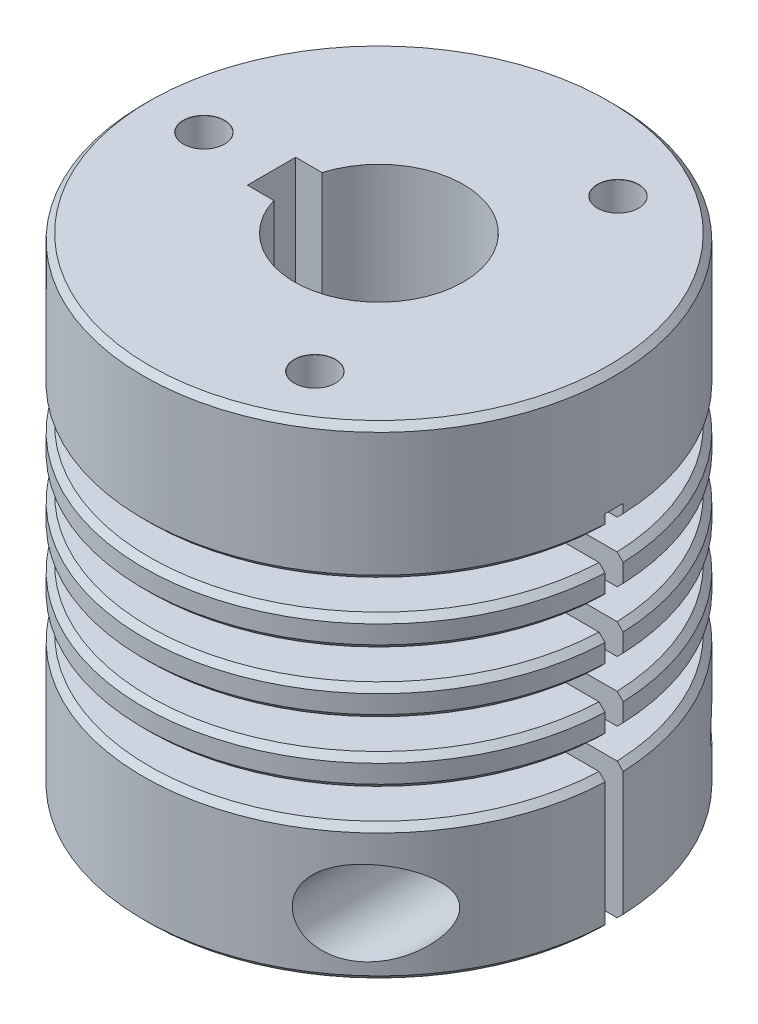
SolidWorks part; units mm, degrees
material "6061-T6 (SS)"
ref_plane "Front Plane" through (0, 0, 0) normal (0, 0, 1) x (1, 0, 0)
ref_plane "Top Plane" through (0, 0, 0) normal (0, 1, 0) x (1, 0, 0)
ref_plane "Right Plane" through (0, 0, 0) normal (1, 0, 0) x (0, 0, -1)
sketch "Sketch3" plane through (0, 0, 0) normal (0, 1, 0) x (1, 0, 0)
  line L0 (-14, 0) -> (-17.8, 0) construction
  line L1 (-17.8, 4) -> (-17.8, -4)
  line L2 (-17.8, 4) -> (-10.3, 4)
  line L3 (-17.8, -4) -> (-10.3, -4)
  line L4 (-10.3, 4) -> (-10.3, -4)
  line L5 (-14, 0) -> (-10.3, 0) construction
  circle A0 centre (0, 0) radius 39 construction
  circle A1 centre (0, 0) radius 14 construction
  point P9 (-17.8, 0)
  dimension "D1" = 78
  dimension "D2" = 28
  dimension "D3" = 8
  dimension "D4" = 3.8
  dimension "D5" = 3.7
sketch "Sketch4" plane through (0, 0, 0) normal (0, 1, 0) x (1, 0, 0)
  line L0 (-17.8, 4) -> (-17.8, -4) construction
  line L1 (-17.8, 4) -> (-17.8, -4)
  line L2 (-17.8, 4) -> (-13.4164, 4)
  line L3 (-17.8, 4) -> (-10.3, 4) construction
  line L4 (-17.8, -4) -> (-13.4164, -4)
  circle A0 centre (0, 0) radius 14 construction
  circle A1 centre (0, 0) radius 39 construction
  arc A2 (-13.4164, -4) -> (-13.4164, 4) centre (0, 0) ccw
  circle A3 centre (0, 0) radius 39
extrude "Boss-Extrude1" add sketch "Sketch4" along normal blind 80
sketch "Sketch7" plane through (0, 0, 0) normal (0, -1, 0) x (1, 0, 0)
  line L0 (14, 0) -> (39, 0) construction
  line L2 (11.5, 1.5) -> (41.5, 1.5)
  line L3 (11.5, 1.5) -> (11.5, -1.5)
  line L4 (11.5, -1.5) -> (41.5, -1.5)
  line L5 (41.5, 1.5) -> (41.5, -1.5)
  line L6 (11.5, 1.5) -> (41.5, -1.5) construction
  line L7 (11.5, -1.5) -> (41.5, 1.5) construction
  arc A0 (-13.4164, -4) -> (-13.4164, 4) centre (0, 0) ccw construction
  circle A1 centre (0, 0) radius 39 construction
  point P8 (26.5, 0)
  dimension "D1" = 3
  dimension "D2" = 30
extrude "Cut-Extrude1" cut sketch "Sketch7" against normal blind 60
sketch "Sketch9" plane through (0, 0, 0) normal (0, 0, 1) x (1, 0, 0)
  line L0 (26.4453, 0) -> (26.4453, 10) construction
  line L5 (13.9194, 60) -> (13.9194, 0)
  line L6 (13.9194, 0) -> (38.9711, 0)
  line L7 (38.9711, 0) -> (38.9711, 60)
  line L10 (13.9194, 0) -> (38.9711, 0) construction
  line L17 (38.9711, 60) -> (13.9194, 60)
  circle A0 centre (26.4453, 10) radius 3.4
  dimension "D2" = 6.8
  dimension "D3" = 10
  dimension "D1" = 0
extrude "Cut-Extrude2" cut sketch "Sketch9" against normal through all
sketch "Sketch10" plane through (0, 0, 0) normal (0, 0, 1) x (1, 0, 0)
  circle A1 centre (26.4453, 10) radius 4
  point P0 (26.4453, 10)
  dimension "D1" = 8
extrude "Cut-Extrude3" cut sketch "Sketch10" along normal through all
sketch "Sketch11" plane through (0, 0, 0) normal (0, 0, 1) x (1, 0, 0)
  circle A0 centre (26.4453, 10) radius 7
  point P0 (26.4453, 10)
  dimension "D1" = 14
extrude "Cut-Extrude4" cut sketch "Sketch11" along normal through all from offset 10
sketch "Sketch12" plane through (0, 80, 0) normal (0, 1, 0) x (1, 0, 0)
  circle A0 centre (0, 0) radius 29 construction
  circle A1 centre (-29, 0) radius 3.4
  circle A2 centre (14.5, 25.1147) radius 3.4
  circle A3 centre (14.5, -25.1147) radius 3.4
  point P3 (-29, 0)
  point P7 (14.5, 25.1147)
  point P9 (14.5, -25.1147)
  point P21 (-2.3959, 7.9863)
  dimension "D1" = 58
  dimension "D2" = 6.8
  dimension "D3" = 3
thread "Thread3" [suppressed] pitch 1.25 start angle 0, offset 1, length 25, pitch 1.25, diameter 6.8
ref_plane "Plane3" through (23.0453, 10, -0.5) normal (0, -1, 0) x (-1, 0, 0)
sketch "Thread Profile3" plane through (23.0453, 10, -0.5) normal (0, -1, 0) x (-1, 0, 0)
  line L0 (0, 0) -> (0, 1.25) construction
  line L1 (0, 0) -> (0.6766, 0.3906)
  line L2 (0.6766, 0.3906) -> (0.6766, 0.5469)
  line L3 (0.6766, 0.5469) -> (0, 0.9375)
  line L4 (0.6766, 0.4687) -> (0, 0.4687) construction
  line L11 (0, 0) -> (0, 0.9375)
  point P2 (0, 0)
  dimension "Pitch" = 1.25
  dimension "Profile_Angle" = 60
  dimension "Profile_Land" = 0.1562
  dimension "Profile_Height" = 0.6766
sketch "Sketch14" plane through (0, 0, 0) normal (0, 0, 1) x (1, 0, 0)
  line L0 (0, 0) -> (0, 80) construction
  line L1 (0, 55) -> (-39, 55) construction
  line L2 (39, 80) -> (-39, 80) construction
  line L3 (-39, 80) -> (-39, 0) construction
  line L9 (-39, 57.5) -> (-29, 57.5)
  line L10 (-39, 57.5) -> (-39, 52.5)
  line L11 (-39, 52.5) -> (-29, 52.5)
  line L12 (-29, 57.5) -> (-29, 52.5)
  line L13 (-39, 57.5) -> (-29, 52.5) construction
  line L14 (-39, 52.5) -> (-29, 57.5) construction
  point P8 (-39, 55)
  dimension "D2" = 10
  dimension "D1" = 5
  dimension "D3" = 55
revolve "Cut-Revolve5" cut sketch "Sketch14" angle 360 about L0
pattern_linear "LPattern2" count 4 spacing 10 along (0, -1, 0) of "Cut-Revolve5"
chamfer "Chamfer1" distance 1 angle 45 10 edges at (-39, 0, 0) (-39, 22.5, 0) (-39, 27.5, 0) (-39, 32.5, 0) (-39, 37.5, 0) (-39, 42.5, 0) (-39, 47.5, 0) (-39, 52.5, 0) (-39, 57.5, 0) (0, 80, 39)
hole_wizard "Ø6.8 (6.8) Diameter Hole1" positions "Sketch12" profile "Sketch17" hole size "Ø6.8" standard "ISO"
sketch "Sketch17" plane through (14.5, 80, 25.1147) normal (1, 0, 0) x (0, 0, 1)
  line L0 (0, 0) -> (0, 22.0429)
  line L1 (0, 22.0429) -> (3.4, 20)
  line L2 (3.4, 20) -> (3.4, 0.025)
  line L3 (3.4, 0.025) -> (3.425, 0)
  line L5 (3.425, 0) -> (0, 0)
  line L6 (-3.4, 0.025) -> (-3.425, 0) construction
  line L10 (0, 22.0429) -> (-3.4, 20) construction
  line L11 (0, -6.35) -> (0, 107.95) construction
  dimension "Hole Dia." = 6.8
  dimension "Hole Depth" = 20
  dimension "Near C'Sink Dia." = 6.85
  dimension "Near C'Sink Angle" = 90
  dimension "Drill Angle" = 118
thread "Thread1" [suppressed] pitch 1.25 start angle 0, offset 2, length 0, pitch 1.25, diameter 6.8
ref_plane "Plane1" through (-32.4, 81.975, 0) normal (0, 0, 1) x (-1, 0, 0)
sketch "Thread Profile1" plane through (-32.4, 81.975, 0) normal (0, 0, 1) x (-1, 0, 0)
  line L0 (0, 0) -> (0, 1.25) construction
  line L1 (0, 0) -> (0.6766, 0.3906)
  line L2 (0.6766, 0.3906) -> (0.6766, 0.5469)
  line L3 (0.6766, 0.5469) -> (0, 0.9375)
  line L4 (0.6766, 0.4687) -> (0, 0.4687) construction
  line L11 (0, 0) -> (0, 0.9375)
  point P2 (0, 0)
  dimension "Pitch" = 1.25
  dimension "Profile_Angle" = 60
  dimension "Profile_Land" = 0.1562
  dimension "Profile_Height" = 0.6766
pattern_circular "CirPattern1" [suppressed] count 3 over 360
